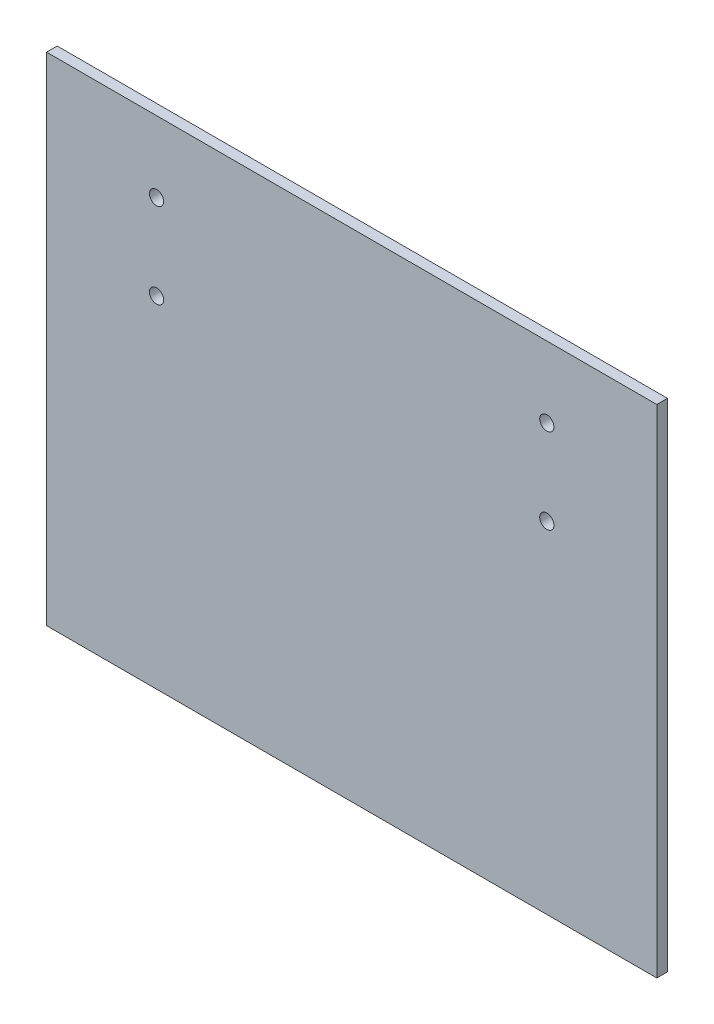
SolidWorks part; units mm, degrees
material "A-玻璃纤维"
ref_plane "前视基准面" through (0, 0, 0) normal (0, 0, 1) x (1, 0, 0)
ref_plane "上视基准面" through (0, 0, 0) normal (0, 1, 0) x (1, 0, 0)
ref_plane "右视基准面" through (0, 0, 0) normal (1, 0, 0) x (0, 0, -1)
other "Configuration Table"
sketch "草图1" plane through (0, 0, 0) normal (0, 0, 1) x (1, 0, 0)
  line L1 (0, 0) -> (172, 0)
  line L2 (0, 0) -> (0, -140)
  line L3 (0, -140) -> (172, -140)
  line L4 (172, 0) -> (172, -140)
  dimension "D1" = 172
  dimension "D2" = 140
extrude "凸台-拉伸1" add sketch "草图1" along normal blind 3
sketch "草图2" plane through (0, 0, 3) normal (0, 0, 1) x (1, 0, 0)
  line L0 (86, 0) -> (86, -183.257) construction
  line L1 (172, 0) -> (0, 0) construction
  circle A0 centre (31, -20) radius 2
  circle A1 centre (31, -44) radius 2
  circle A2 centre (141, -44) radius 2
  circle A3 centre (141, -20) radius 2
  dimension "D1" = 4
  dimension "D2" = 2
  dimension "D3" = 24
  dimension "D4" = 55
  dimension "D5" = 20
extrude "切除-拉伸1" cut sketch "草图2" against normal blind 37
